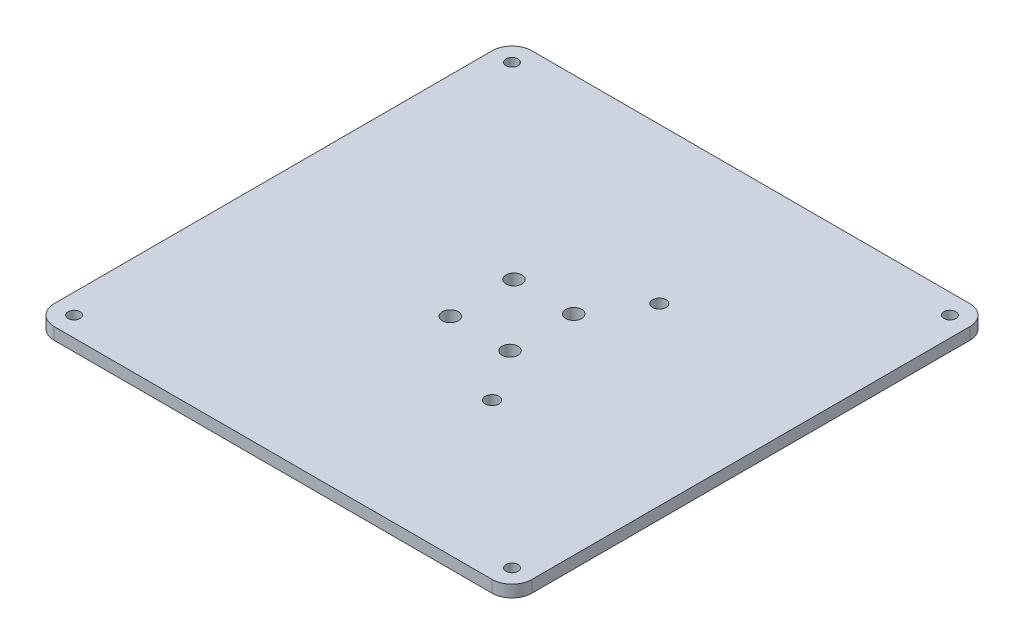
SolidWorks part; units mm, degrees
material "ABS"
ref_plane "Alzado" through (0, 0, 0) normal (0, 0, 1) x (1, 0, 0)
ref_plane "Planta" through (0, 0, 0) normal (0, 1, 0) x (1, 0, 0)
ref_plane "Vista lateral" through (0, 0, 0) normal (1, 0, 0) x (0, 0, -1)
sketch "Sketch1" plane through (0, 0, 0) normal (0, 1, 0) x (1, 0, 0)
  line L1 (-7.5, -8) -> (7.5, -8) construction
  line L2 (-7.5, -8) -> (-7.5, 8) construction
  line L3 (-7.5, 8) -> (7.5, 8) construction
  line L4 (7.5, -8) -> (7.5, 8) construction
  line L5 (-7.5, -8) -> (7.5, 8) construction
  line L6 (-7.5, 8) -> (7.5, -8) construction
  line L7 (-60, -60) -> (60, -60)
  line L8 (-60, -60) -> (-60, 60)
  line L9 (-60, 60) -> (60, 60)
  line L10 (60, -60) -> (60, 60)
  circle A0 centre (-7.5, -8) radius 2
  circle A1 centre (7.5, 8) radius 2
  circle A2 centre (7.5, -8) radius 2
  circle A3 centre (-7.5, 8) radius 2
  point P0 (0, 0)
  point P10 (0, 0)
  point P16 (-60, 0)
  point P17 (0, -60)
  dimension "D3" = 4
  dimension "D1" = 16
  dimension "D2" = 15
  dimension "D4" = 120
  dimension "D5" = 120
extrude "Boss-Extrude1" add sketch "Sketch1" along normal blind 3
fillet "Fillet1" radius 5 4 edges at (-60, 1.5, -60) (60, 1.5, -60) (60, 1.5, 60) (-60, 1.5, 60)
sketch "Sketch2" plane through (0, 3, 0) normal (0, 1, 0) x (1, 0, 0)
  line L0 (-55, 55) -> (-55, 60) construction
  line L1 (-55, 55) -> (-60, 55) construction
  circle A0 centre (-55, 55) radius 1.5
  dimension "D1" = 3
extrude "Cut-Extrude1" cut sketch "Sketch2" against normal through all
mirror "Mirror3" about plane through (0, 0, 0) normal (0, 0, 1) of "Cut-Extrude1" second plane through (0, 0, 0) second plane normal (1, 0, 0)
sketch "Sketch3" plane through (0, 3, 0) normal (0, 1, 0) x (1, 0, 0)
  line L0 (16, 21) -> (16, -21) construction
  circle A2 centre (16, 21) radius 1.7
  circle A3 centre (16, -21) radius 1.7
  point P4 (16, 0)
  dimension "D2" = 42
  dimension "D1" = 3.4
  dimension "D3" = 16
extrude "Cut-Extrude2" cut sketch "Sketch3" against normal through all
